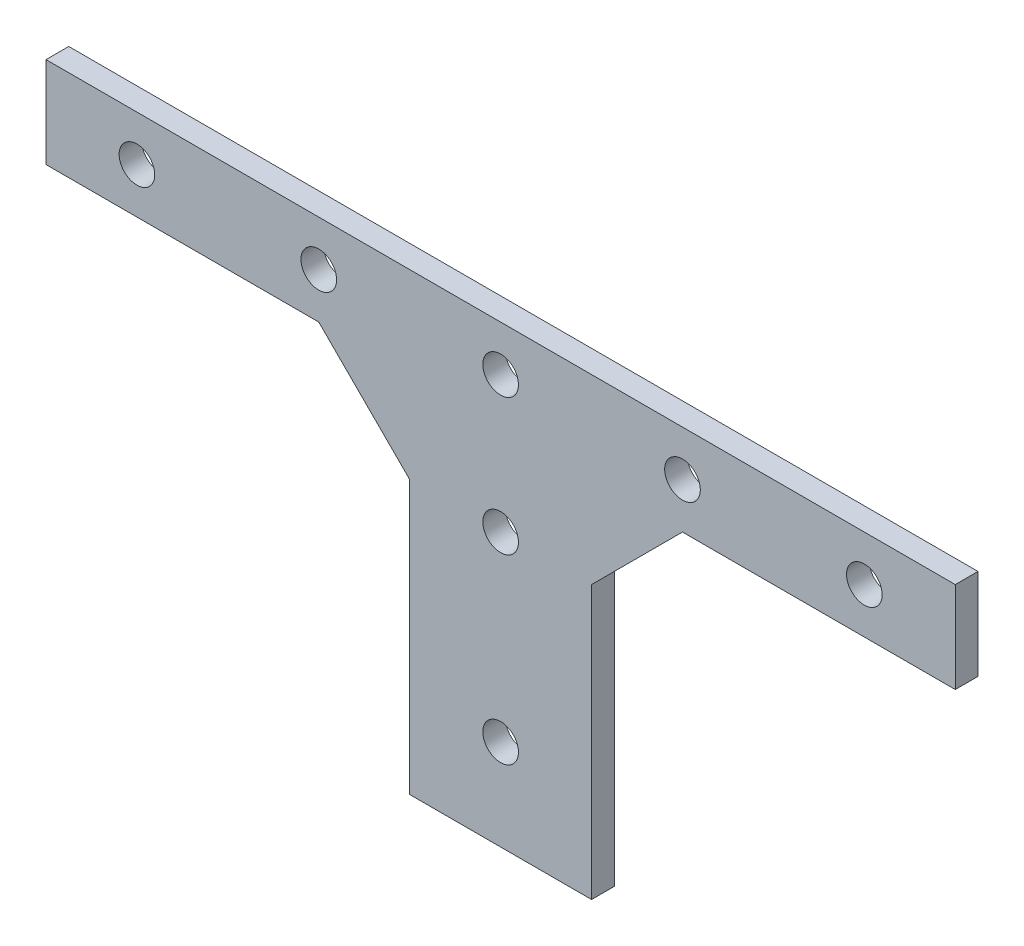
SolidWorks part; units mm, degrees
material "6061 Alloy"
ref_plane "Front Plane" through (0, 0, 0) normal (0, 0, 1) x (1, 0, 0)
ref_plane "Top Plane" through (0, 0, 0) normal (0, 1, 0) x (1, 0, 0)
ref_plane "Right Plane" through (0, 0, 0) normal (1, 0, 0) x (0, 0, -1)
sketch "Sketch1" plane through (0, 0, 0) normal (0, 0, 1) x (1, 0, 0)
  line L0 (41.275, -25.4) -> (41.275, -63.5)
  line L2 (41.275, -63.5) -> (66.675, -63.5)
  line L4 (66.675, -63.5) -> (66.675, -25.4)
  line L5 (79.375, -12.7) -> (117.475, -12.7)
  line L7 (117.475, -12.7) -> (117.475, 0)
  line L9 (117.475, 0) -> (-9.525, 0)
  line L10 (-9.525, 0) -> (-9.525, -12.7)
  line L11 (-9.525, -12.7) -> (28.575, -12.7)
  line L13 (66.675, -25.4) -> (79.375, -12.7)
  line L14 (53.975, -12.7) -> (53.975, -25.4) construction
  line L15 (41.275, -25.4) -> (28.575, -12.7)
  line L16 (53.975, -63.5) -> (53.975, 0) construction
  line L17 (117.475, -6.35) -> (-9.525, -6.35) construction
  line L18 (117.475, -6.35) -> (104.775, -6.35) construction
  line L19 (104.775, -6.35) -> (79.375, -6.35) construction
  line L20 (79.375, -6.35) -> (53.975, -6.35) construction
  line L21 (53.975, -6.35) -> (28.575, -6.35) construction
  line L22 (28.575, -6.35) -> (3.175, -6.35) construction
  line L23 (53.975, -25.4) -> (53.975, -50.8) construction
  dimension "D3" = 127
extrude "Boss-Extrude1" add sketch "Sketch1" along normal blind 3.175
hole_wizard "#10 Clearance Hole1" positions "Sketch4" profile "Sketch5" hole size "#10" standard "ANSI Inch" end condition through all
sketch "Sketch4" plane through (0, 0, 3.175) normal (0, 0, 1) x (1, 0, 0)
  point P0 (3.175, -6.35)
  point P3 (28.575, -6.35)
  point P6 (53.975, -6.35)
  point P13 (104.775, -6.35)
  point P16 (53.975, -25.4)
  point P19 (53.975, -50.8)
  point P22 (79.375, -6.35)
sketch "Sketch5" plane through (3.175, -6.35, 3.175) normal (1, 0, 0) x (0, -1, 0)
  line L0 (0, 0) -> (0, 3.175)
  line L1 (0, 3.175) -> (2.4892, 3.175)
  line L2 (2.4892, 3.175) -> (2.4892, 0)
  line L5 (2.4892, 0) -> (0, 0)
  line L11 (0, -6.35) -> (0, 107.95) construction
  dimension "Thru Hole Dia." = 4.9784
  dimension "Thru Hole Depth" = 3.175
